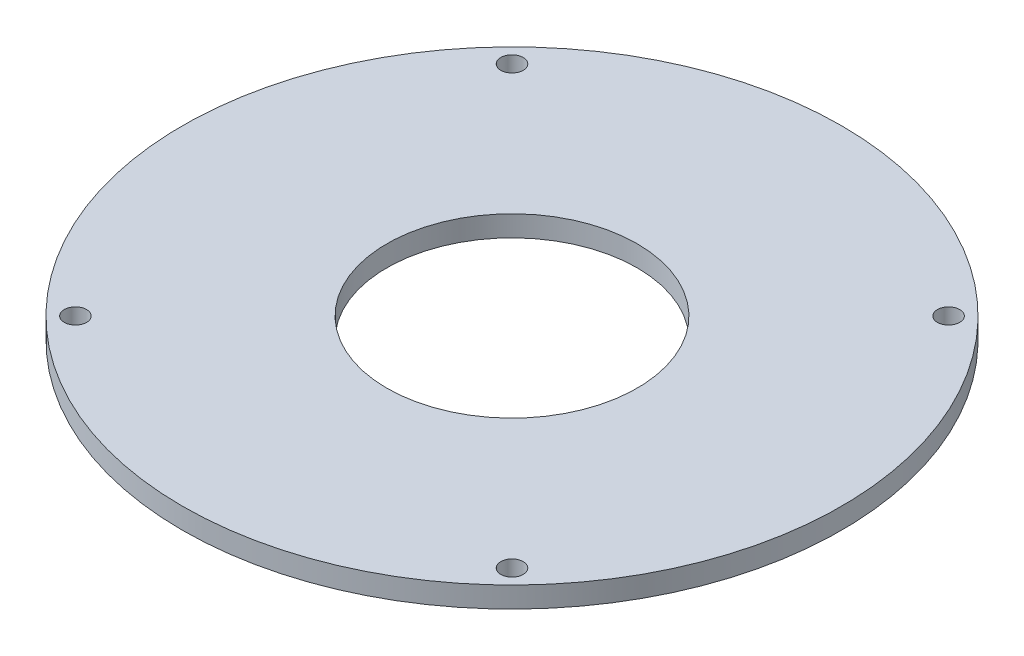
SolidWorks part; units mm, degrees
ref_plane "Front Plane" through (0, 0, 0) normal (0, 0, 1) x (1, 0, 0)
ref_plane "Top Plane" through (0, 0, 0) normal (0, 1, 0) x (1, 0, 0)
ref_plane "Right Plane" through (0, 0, 0) normal (1, 0, 0) x (0, 0, -1)
sketch "Sketch1" plane through (0, 0, 0) normal (0, 1, 0) x (1, 0, 0)
  line L1 (-33.2269, 33.2269) -> (33.2269, 33.2269) construction
  line L2 (-33.2269, 33.2269) -> (-33.2269, -33.2269) construction
  line L3 (-33.2269, -33.2269) -> (33.2269, -33.2269) construction
  line L4 (33.2269, 33.2269) -> (33.2269, -33.2269) construction
  line L5 (-33.2269, 33.2269) -> (33.2269, -33.2269) construction
  line L6 (-33.2269, -33.2269) -> (33.2269, 33.2269) construction
  circle A0 centre (0, 0) radius 50.165
  circle A1 centre (0, 0) radius 19.05
  dimension "D1" = 100.33
  dimension "D3" = 38.1
  dimension "D2" = 93.98
extrude "Boss-Extrude1" add sketch "Sketch1" along normal mid plane 3.175
hole_wizard "M3 Clearance Hole1" positions "Sketch2" profile "Sketch3" hole size "M3" standard "ISO" end condition through all
sketch "Sketch2" plane through (0, 1.5875, 0) normal (0, 1, 0) x (1, 0, 0)
  point P0 (-33.2269, -33.2269)
  point P3 (-33.2269, 33.2269)
  point P6 (33.2269, 33.2269)
  point P9 (33.2269, -33.2269)
sketch "Sketch3" plane through (-33.2269, 1.5875, 33.2269) normal (1, 0, 0) x (0, 0, 1)
  line L0 (0, 0) -> (0, 3.175)
  line L1 (0, 3.175) -> (1.7, 3.175)
  line L2 (1.7, 3.175) -> (1.7, 0)
  line L5 (1.7, 0) -> (0, 0)
  line L11 (0, -6.35) -> (0, 107.95) construction
  dimension "Thru Hole Dia." = 3.4
  dimension "Thru Hole Depth" = 3.175
